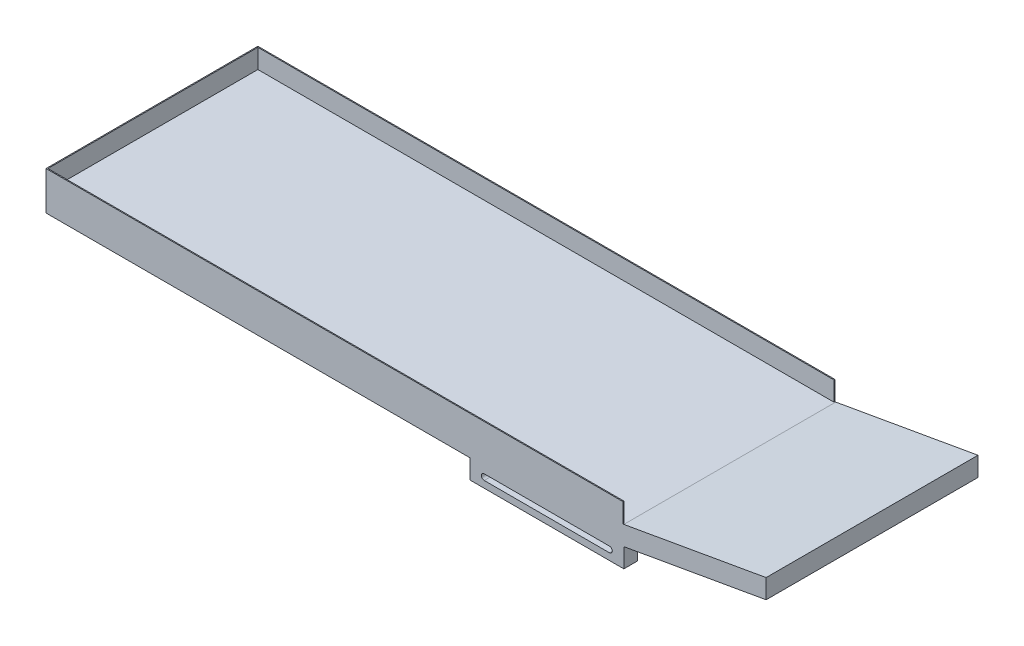
SolidWorks part; units mm, degrees
ref_plane "Płaszczyzna przednia" through (0, 0, 0) normal (0, 0, 1) x (1, 0, 0)
ref_plane "Płaszczyzna górna" through (0, 0, 0) normal (0, 1, 0) x (1, 0, 0)
ref_plane "Płaszczyzna prawa" through (0, 0, 0) normal (1, 0, 0) x (0, 0, -1)
sketch "Szkic1" plane through (0, 0, 0) normal (0, 0, 1) x (1, 0, 0)
  line L0 (600, 0) -> (747.7212, 26.0472)
  line L1 (0, 0) -> (600, 0)
  line L2 (0, 0) -> (0, 20)
  line L3 (0, 20) -> (600, 20)
  line L5 (600, 20) -> (747.7212, 46.0472)
  line L6 (747.7212, 46.0472) -> (747.7212, 26.0472)
  dimension "D1" = 20
  dimension "D2" = 600
  dimension "D3" = 10
  dimension "D4" = 150
extrude "Dodanie-wyciągnięcie1" add sketch "Szkic1" along normal blind 220
sketch "Szkic2" plane through (0, 20, 0) normal (0, 1, 0) x (1, 0, 0)
  line L0 (599, -1) -> (1, -1)
  line L1 (1, -1) -> (1, -219)
  line L2 (1, -219) -> (599, -219)
  line L4 (600, 0) -> (0, 0)
  line L5 (0, 0) -> (0, -220)
  line L6 (0, -220) -> (600, -220)
  line L7 (600, -220) -> (600, 0)
  line L8 (600, 0) -> (0, 0)
  line L9 (0, 0) -> (0, -220)
  line L10 (0, -220) -> (600, -220)
  line L12 (599, -219) -> (599, -1) construction
  line L13 (600, -220) -> (600, 0) construction
  line L14 (599, -1) -> (599, 0)
  line L15 (599, -219) -> (599, -220)
  line M6 (0, 0) -> (0, -220)
  line M7 (0, -220) -> (600, -220)
  dimension "D1" = 0
  dimension "D2" = 1
extrude "Dodanie-wyciągnięcie2" add sketch "Szkic2" along normal blind 20 contours L15 L2 L1 L0 L14 L8 M6 M7
sketch "Szkic3" plane through (0, 0, 0) normal (0, -1, 0) x (1, 0, 0)
  line L1 (600, 220) -> (440, 220)
  line L2 (600, 220) -> (600, 206)
  line L3 (600, 206) -> (440, 206)
  line L4 (440, 220) -> (440, 206)
  line L5 (600, 0) -> (440, 0)
  line L6 (600, 0) -> (600, 14)
  line L7 (600, 14) -> (440, 14)
  line L8 (440, 0) -> (440, 14)
  dimension "D1" = 14
  dimension "D2" = 160
extrude "Dodanie-wyciągnięcie3" add sketch "Szkic3" along normal blind 20
sketch "Szkic4" plane through (0, 0, 220) normal (0, 0, 1) x (1, 0, 0)
  line L0 (585, -10) -> (455, -10) construction
  line L1 (585, -13) -> (455, -13)
  line L2 (585, -7) -> (455, -7)
  line L3 (600, -20) -> (440, -20) construction
  line L4 (600, -20) -> (600, 0) construction
  line L5 (440, -20) -> (440, 0) construction
  arc A0 (585, -13) -> (585, -7) centre (585, -10) ccw
  arc A1 (455, -7) -> (455, -13) centre (455, -10) ccw
  point P2 (520, -10)
  dimension "D1" = 10
  dimension "D2" = 6
  dimension "D3" = 15
  dimension "D4" = 15
extrude "Wytnij-wyciągnięcie1" cut sketch "Szkic4" against normal through all
